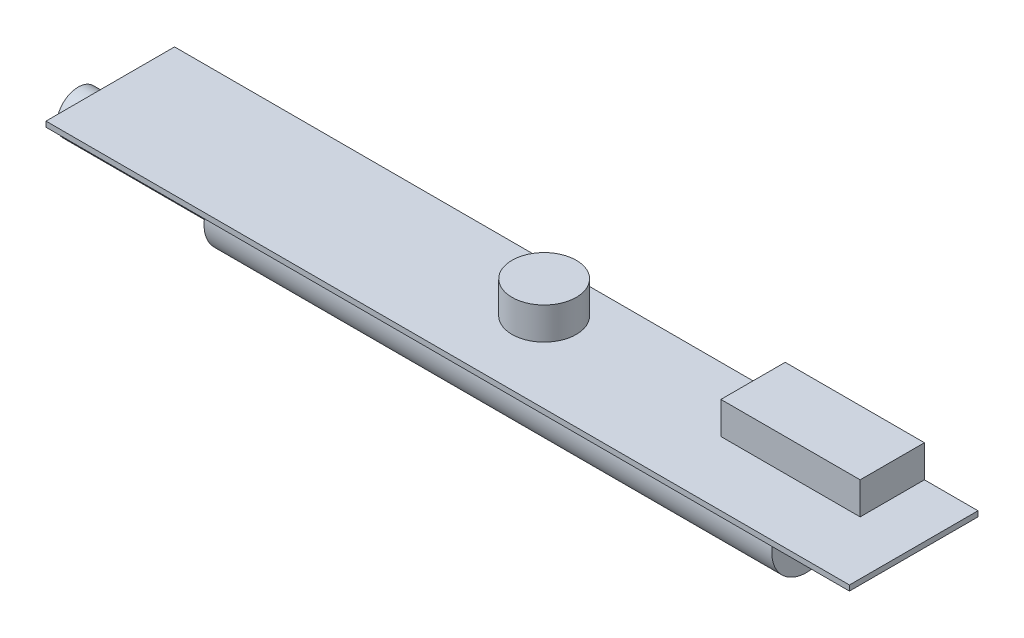
SolidWorks part; units mm, degrees
ref_plane "Front" through (0, 0, 0) normal (0, 0, 1) x (1, 0, 0)
ref_plane "Top" through (0, 0, 0) normal (0, 1, 0) x (1, 0, 0)
ref_plane "Right" through (0, 0, 0) normal (1, 0, 0) x (0, 0, -1)
sketch "Sketch1" plane through (0, 0, 0) normal (0, 1, 0) x (1, 0, 0)
  line L1 (-37.5, 6) -> (37.5, 6)
  line L2 (-37.5, 6) -> (-37.5, -6)
  line L3 (-37.5, -6) -> (37.5, -6)
  line L4 (37.5, 6) -> (37.5, -6)
  line L5 (-37.5, 6) -> (37.5, -6) construction
  line L6 (-37.5, -6) -> (37.5, 6) construction
  point P0 (0, 0)
  dimension "D1" = 12
  dimension "D2" = 75
extrude "Boss-Extrude1" add sketch "Sketch1" along normal blind 0.5
sketch "Sketch2" plane through (0, 0.5, 0) normal (0, 1, 0) x (1, 0, 0)
  line L0 (37.5, 6) -> (-37.5, 6) construction
  line L1 (19.5, 6) -> (32.5, 6)
  line L2 (19.5, 6) -> (19.5, 0)
  line L3 (19.5, 0) -> (32.5, 0)
  line L4 (32.5, 6) -> (32.5, 0)
  line L5 (37.5, -6) -> (37.5, 6) construction
  circle A0 centre (1.5, 1.5) radius 3
  dimension "D1" = 6
  dimension "D2" = 36
  dimension "D3" = 13
  dimension "D4" = 5
  dimension "D5" = 4.5
extrude "Boss-Extrude2" add sketch "Sketch2" along normal blind 3 separate body
sketch "Sketch3" plane through (37.5, 0, 0) normal (1, 0, 0) x (0, 0, -1)
  line L0 (-6, 0) -> (6, 0) construction
  circle A0 centre (0, -3.25) radius 3.25
  dimension "D1" = 6.5
extrude "Boss-Extrude3" add sketch "Sketch3" against normal blind 53 from offset 10 separate body offset against normal yes
sketch "Sketch4" plane through (-25.5, 0, 0) normal (-1, 0, 0) x (0, 0, 1)
  circle A0 centre (0, -3.25) radius 2
  circle A1 centre (0, -3.25) radius 3.25 construction
  dimension "D1" = 4
extrude "Boss-Extrude4" add sketch "Sketch4" along normal blind 15
